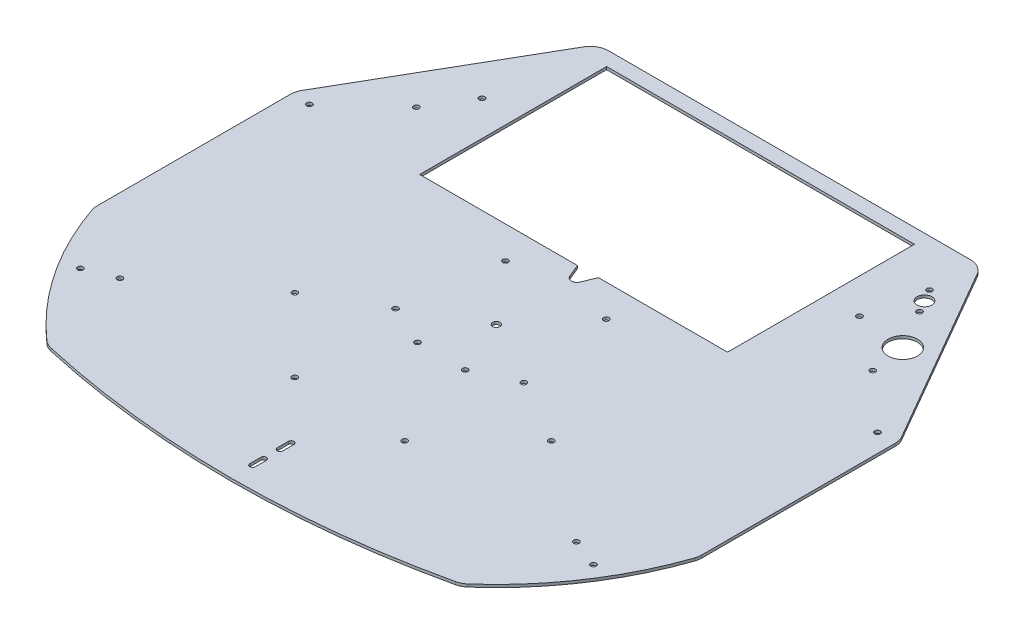
SolidWorks part; units mm, degrees
material "3.0205 (EN-AW 1200)"
ref_plane "Plan de face" through (0, 0, 0) normal (0, 0, 1) x (1, 0, 0)
ref_plane "Plan de dessus" through (0, 0, 0) normal (0, 1, 0) x (1, 0, 0)
ref_plane "Plan de droite" through (0, 0, 0) normal (1, 0, 0) x (0, 0, -1)
sketch "Esquisse1" plane through (0, 0, 0) normal (0, 1, 0) x (1, 0, 0)
  line L2 (0, 0) -> (165, 0) construction
  line L4 (165, -54.557) -> (165, 55.2417)
  line L5 (-165, 55.2417) -> (-104.5177, 160)
  line L6 (-165, -54.557) -> (-165, 55.2417)
  line L9 (0, 160) -> (0, 0) construction
  line L12 (-104.5177, 160) -> (104.5177, 160)
  line L13 (165, 55.2417) -> (104.5177, 160)
  arc A0 (-165, -54.557) -> (-112.9493, -132.0754) centre (0, 0) ccw
  circle A1 centre (158.5, 53.5) radius 6.5 construction
  circle A2 centre (-158.5, 53.5) radius 6.5 construction
  circle A3 centre (158.5, -53.5) radius 6.5 construction
  circle A4 centre (-158.5, -53.5) radius 6.5 construction
  arc A5 (-112.9493, -132.0754) -> (112.9493, -132.0754) centre (0, 355) ccw
  arc A6 (112.9493, -132.0754) -> (165, -54.557) centre (0, 0) ccw
  point P21 (0, -145)
  dimension "D2" = 145
  dimension "D13" = 225.8987
  dimension "D16" = 500
  dimension "D9" = 13
  dimension "D12" = 317
  dimension "D15" = 107
  dimension "D4" = 60
  dimension "D5" = 209.0355
  dimension "D6" = 330
  dimension "D7" = 120.9645
  dimension "D8" = 109.7986
  dimension "D10" = 93.3723
  dimension "D11" = 160
extrude "Boss.-Extru.1" add sketch "Esquisse1" along normal blind 1.5
fillet "Congé1" radius 10 8 edges at (165, 0.75, 54.557) (165, 0.75, -55.2417) (-165, 0.75, 54.557) (-165, 0.75, -55.2417) (104.5177, 0.75, -160) (-104.5177, 0.75, -160) (112.9493, 0.75, 132.0754) (-112.9493, 0.75, 132.0754)
sketch "Esquisse4" plane through (0, 1.5, 0) normal (0, 1, 0) x (1, 0, 0)
  line L0 (98.7442, 160) -> (-98.7442, 160) construction
  line L1 (-91.816, 152) -> (76.184, 152)
  line L2 (-91.816, 152) -> (-91.816, 50)
  line L3 (-91.816, 50) -> (-5.7325, 50)
  line L4 (76.184, 152) -> (76.184, 50)
  line L5 (-107.4045, 155) -> (-163.6603, 57.5622) construction
  line L6 (-2.7716, 42.8519) -> (-5.7325, 50)
  line L7 (0, 44) -> (0, 0) construction
  line L8 (2.7716, 42.8519) -> (5.7325, 50)
  line L9 (5.7325, 50) -> (76.184, 50)
  line L10 (163.6603, 57.5622) -> (107.4045, 155) construction
  line L11 (98.7442, 160) -> (-98.7442, 160) construction
  line L12 (101.9225, 134.4952) -> (109.4225, 121.5048) construction
  line L13 (-7.816, 152) -> (-7.816, 50) construction
  circle A0 centre (121.8383, 100) radius 8
  circle A1 centre (105.6725, 128) radius 4
  arc A2 (-2.7716, 42.8519) -> (2.7716, 42.8519) centre (0, 44) ccw
  circle A3 centre (101.9225, 134.4952) radius 1.5
  circle A4 centre (109.4225, 121.5048) radius 1.5
  circle A5 centre (-110.816, 103) radius 1.5
  circle A6 centre (95.184, 103) radius 1.5
  circle A7 centre (-27.5, 32.5) radius 1.5
  circle A8 centre (35, -20) radius 1.5
  circle A9 centre (27.5, 32.5) radius 1.5
  circle A10 centre (-13, -30) radius 1.5
  circle A11 centre (0, 0) radius 2
  circle A12 centre (-35, -20) radius 1.5
  circle A13 centre (13, -30) radius 1.5
  circle A14 centre (155, 53) radius 1.5
  circle A15 centre (140, -87) radius 1.5
  circle A16 centre (-140, -87) radius 1.5
  circle A17 centre (-155, 53) radius 1.5
  dimension "D8" = 16
  dimension "D5" = 6
  dimension "D6" = 44
  dimension "D9" = 15
  dimension "D10" = 60
  dimension "D11" = 8
  dimension "D12" = 3
  dimension "D15" = 32
  dimension "D16" = 206
  dimension "D17" = 3
  dimension "D18" = 49
  dimension "D19" = 3
  dimension "D23" = 20
  dimension "D24" = 55
  dimension "D25" = 32.5
  dimension "D26" = 4
  dimension "D27" = 3
  dimension "D28" = 155
  dimension "D29" = 53
  dimension "D30" = 87
  dimension "D1" = 102
  dimension "D2" = 168
  dimension "D3" = 8
  dimension "D4" = 15
  dimension "D7" = 45
  dimension "D13" = 15
  dimension "D14" = 15
  dimension "D20" = 13
  dimension "D21" = 30
  dimension "D22" = 35
  dimension "D31" = 140
extrude "Enlèv. mat.-Extru.3" cut sketch "Esquisse4" against normal blind 3
sketch "Esquisse5" plane through (0, 1.5, 0) normal (0, 1, 0) x (1, 0, 0)
  line L0 (0, -112) -> (0, -118) construction
  line L1 (1.5, -112) -> (1.5, -118)
  line L2 (-1.5, -112) -> (-1.5, -118)
  line L3 (0, -127) -> (0, -133) construction
  line L4 (1.5, -127) -> (1.5, -133)
  line L5 (-1.5, -127) -> (-1.5, -133)
  line L6 (0, 0) -> (0, -115) construction
  arc A0 (1.5, -112) -> (-1.5, -112) centre (0, -112) ccw
  arc A1 (-1.5, -118) -> (1.5, -118) centre (0, -118) ccw
  arc A2 (1.5, -127) -> (-1.5, -127) centre (0, -127) ccw
  arc A3 (-1.5, -133) -> (1.5, -133) centre (0, -133) ccw
  circle A4 centre (-30, -80) radius 1.5
  circle A5 centre (30, -80) radius 1.5
  point P3 (0, -115)
  point P8 (0, -130)
  dimension "D5" = 3
  dimension "D6" = 60
  dimension "D7" = 80
  dimension "D1" = 3
  dimension "D2" = 6
  dimension "D3" = 15
  dimension "D4" = 115
extrude "Enlèv. mat.-Extru.4" cut sketch "Esquisse5" against normal through all
sketch "Esquisse6" plane through (0, 1.5, 0) normal (0, 1, 0) x (1, 0, 0)
  line L0 (0, 0) -> (-124.5426, -80.8789) construction
  line L1 (0, 0) -> (-145.7716, -28.3351) construction
  line L2 (-165, 0) -> (0, 0) construction
  line L3 (-165, 52.5622) -> (-165, -52.9221) construction
  line L4 (0, 0) -> (0, 160) construction
  line L5 (98.7442, 160) -> (-98.7442, 160) construction
  circle A0 centre (-124.5426, -80.8789) radius 1.5
  circle A1 centre (-145.7716, -28.3351) radius 1.5 construction
  circle A2 centre (-145.7716, 28.3351) radius 1.5 construction
  circle A3 centre (-124.5426, 80.8789) radius 1.5
  circle A4 centre (124.5426, -80.8789) radius 1.5
  circle A5 centre (145.7716, -28.3351) radius 1.5 construction
  circle A6 centre (145.7716, 28.3351) radius 1.5 construction
  circle A7 centre (124.5426, 80.8789) radius 1.5
  circle A8 centre (70, -40) radius 1.5
  circle A9 centre (-70, -40) radius 1.5
  dimension "D1" = 4
  dimension "D5" = 3
  dimension "D6" = 140
  dimension "D7" = 40
  dimension "D2" = 22
  dimension "D3" = 148.5
  dimension "D4" = 11
extrude "Enlèv. mat.-Extru.5" cut sketch "Esquisse6" against normal through all
